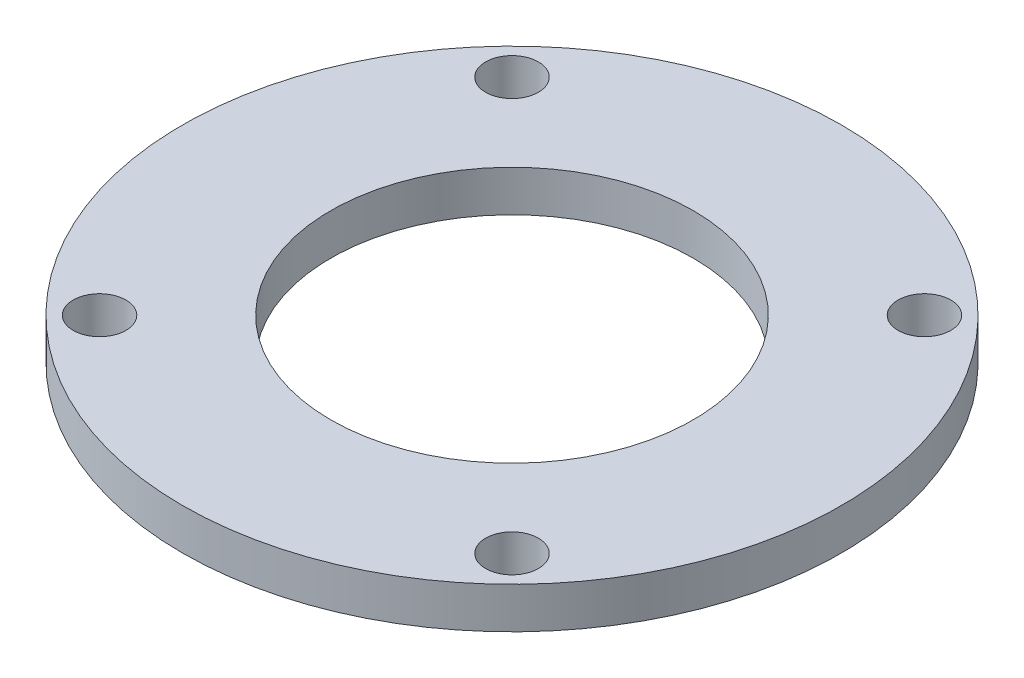
SolidWorks part; units mm, degrees
other "Bearing Retaining Cap"
ref_plane "Front Plane" through (0, 0, 0) normal (0, 0, 1) x (1, 0, 0)
ref_plane "Top Plane" through (0, 0, 0) normal (0, 1, 0) x (1, 0, 0)
ref_plane "Right Plane" through (0, 0, 0) normal (1, 0, 0) x (0, 0, -1)
sketch3d "Cap disc sketch datum points"
  point P0 (-19.0092, -240, -53.2449)
  point P1 (-9.0092, -240, -53.2449)
  point P2 (-19.0092, -240, -63.2449)
ref_plane "Cap disc sketch plane" through (0, -240, 0) normal (0, 1, 0) x (1, 0, 0)
sketch "Cap disc sketch" plane through (0, -240, 0) normal (0, 1, 0) x (1, 0, 0)
  circle A0 centre (-19.0092, 53.2449) radius 20
extrude "Cap disc" add sketch "Cap disc sketch" along normal blind 2.5 separate body
sketch3d "Shaft and spacer clearance sketch datum points"
  point P0 (-19.0092, -240.1, -53.2449)
  point P1 (-9.0092, -240.1, -53.2449)
  point P2 (-19.0092, -240.1, -63.2449)
ref_plane "Shaft and spacer clearance sketch plane" through (0, -240.1, 0) normal (0, 1, 0) x (1, 0, 0)
sketch "Shaft and spacer clearance sketch" plane through (0, -240.1, 0) normal (0, 1, 0) x (1, 0, 0)
  circle A0 centre (-19.0092, 53.2449) radius 11
extrude "Shaft and spacer clearance" cut sketch "Shaft and spacer clearance sketch" along normal blind 2.7
sketch3d "M3 cap clearance pattern sketch datum points"
  point P0 (-19.0092, -240.1, -53.2449)
  point P1 (-9.0092, -240.1, -53.2449)
  point P2 (-19.0092, -240.1, -63.2449)
ref_plane "M3 cap clearance pattern sketch plane" through (0, -240.1, 0) normal (0, 1, 0) x (1, 0, 0)
sketch "M3 cap clearance pattern sketch" plane through (0, -240.1, 0) normal (0, 1, 0) x (1, 0, 0)
  circle A0 centre (-6.4934, 40.7291) radius 1.6
  circle A1 centre (-31.525, 40.7291) radius 1.6
  circle A2 centre (-31.525, 65.7607) radius 1.6
  circle A3 centre (-6.4934, 65.7607) radius 1.6
extrude "M3 cap clearance pattern" cut sketch "M3 cap clearance pattern sketch" along normal blind 2.7
